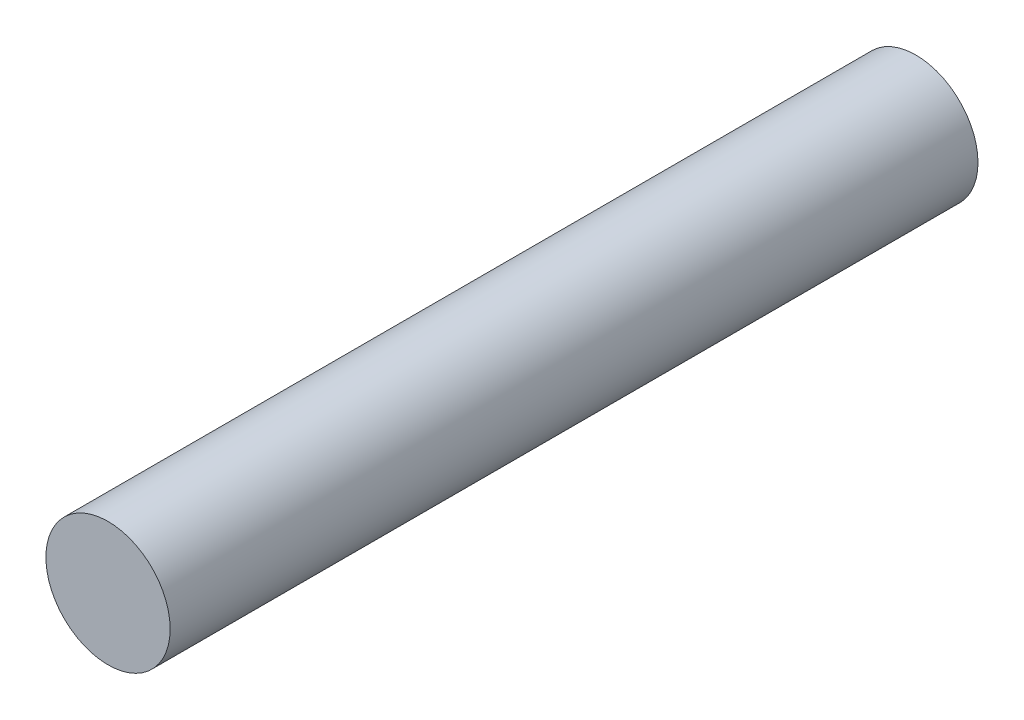
SolidWorks part; units mm, degrees
ref_plane "Plan de face" through (0, 0, 0) normal (0, 0, 1) x (1, 0, 0)
ref_plane "Plan de dessus" through (0, 0, 0) normal (0, 1, 0) x (1, 0, 0)
ref_plane "Plan de droite" through (0, 0, 0) normal (1, 0, 0) x (0, 0, -1)
sketch "Esquisse1" plane through (0, 0, 0) normal (0, 0, 1) x (1, 0, 0)
  circle A0 centre (0, 0) radius 5
  dimension "D1" = 10
extrude "Boss.-Extru.1" add sketch "Esquisse1" along normal blind 65
